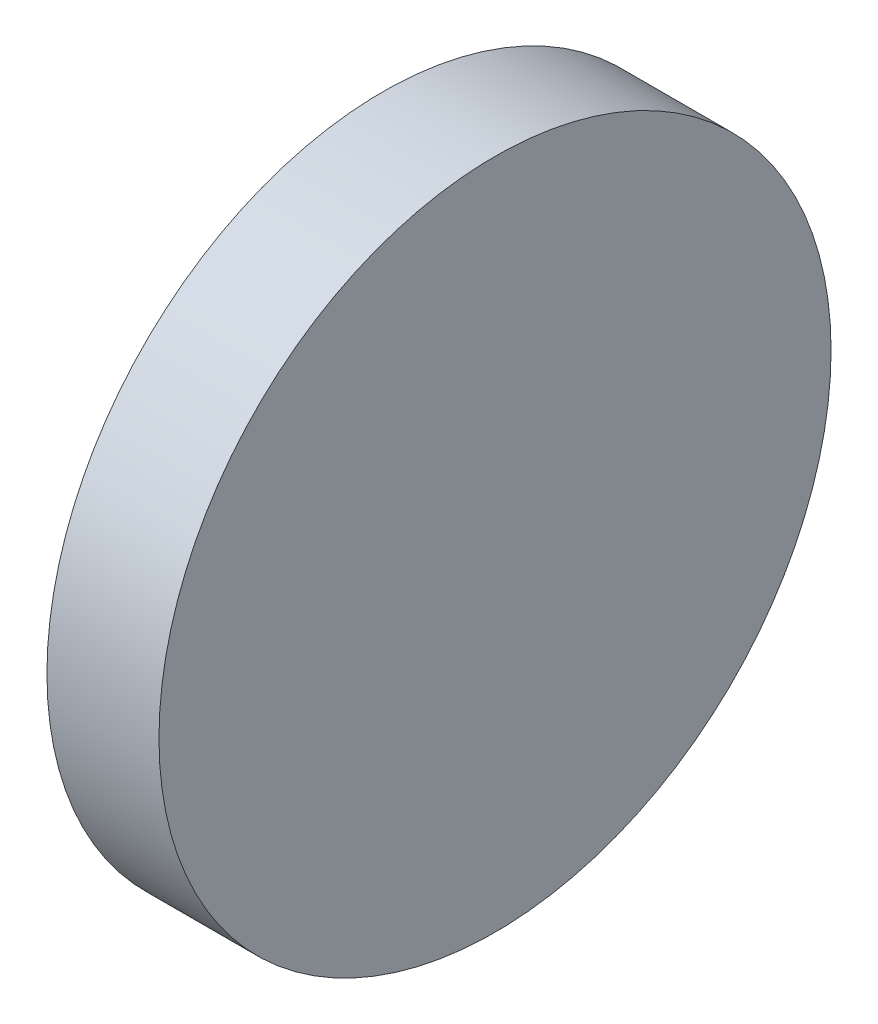
SolidWorks part; units mm, degrees
ref_plane "Front Plane" through (0, 0, 0) normal (0, 0, 1) x (1, 0, 0)
ref_plane "Top Plane" through (0, 0, 0) normal (0, 1, 0) x (1, 0, 0)
ref_plane "Right Plane" through (0, 0, 0) normal (1, 0, 0) x (0, 0, -1)
sketch "Sketch1" plane through (0, 0, 0) normal (1, 0, 0) x (0, 0, -1)
  circle A0 centre (0, 0) radius 38.1
extrude "Boss-Extrude1" add sketch "Sketch1" along normal blind 12.7
ref_plane "Plane1" through (6.35, 0, 0) normal (1, 0, 0) x (0, 0, -1)
ref_plane "Plane2" through (0, 38.1, 0) normal (0, 1, 0) x (-1, 0, 0)
ref_plane "Plane3" through (0, 0, -38.1) normal (0, 0, -1) x (-1, 0, 0)
